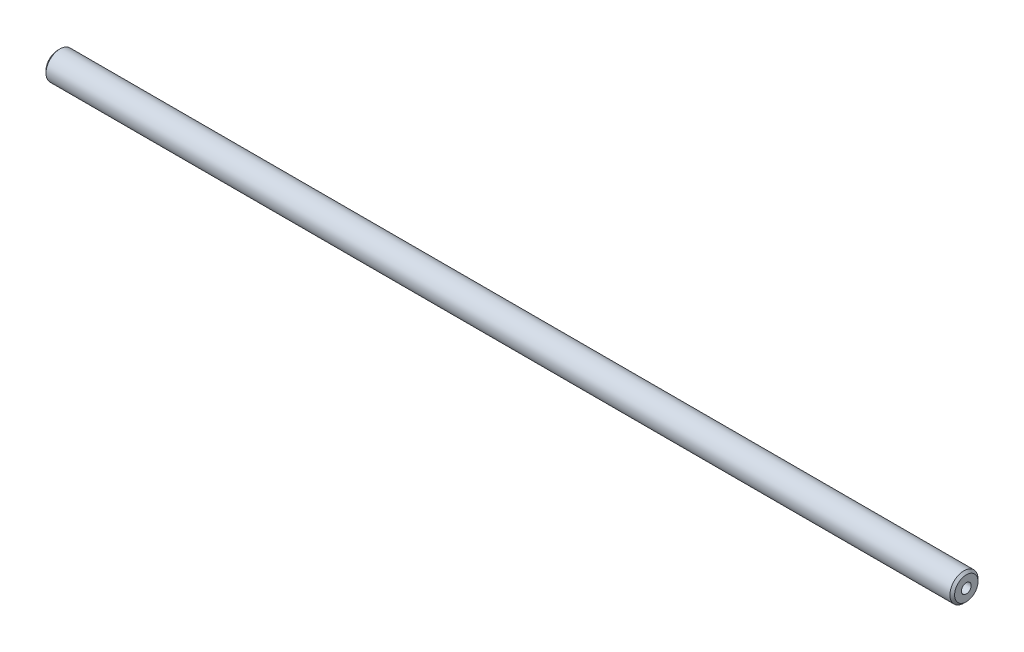
SolidWorks part; units mm, degrees
material "Chrome Stainless Steel"
ref_plane "Front Plane" through (0, 0, 0) normal (0, 0, 1) x (1, 0, 0)
ref_plane "Top Plane" through (0, 0, 0) normal (0, 1, 0) x (1, 0, 0)
ref_plane "Right Plane" through (0, 0, 0) normal (1, 0, 0) x (0, 0, -1)
sketch "Sketch1" plane through (0, 0, 0) normal (1, 0, 0) x (0, 0, -1)
  circle A0 centre (0, 0) radius 6
  dimension "D1" = 12
extrude "Boss-Extrude1" add sketch "Sketch1" along normal blind 388
chamfer "Chamfer1" distance 1 angle 45 2 edges at (388, 0, -6) (0, 0, -6)
hole_wizard "M5 Tapped Hole1" positions "Sketch3" profile "Sketch2" tap size "M5" standard "ISO"
sketch "Sketch3" plane through (388, 0, 0) normal (1, 0, 0) x (0, 0, -1)
  point P1 (0, 0)
sketch "Sketch2" plane through (388, 0, 0) normal (0, 1, 0) x (0, 0, -1)
  line L0 (0, 0) -> (0, 15.2618)
  line L1 (0, 15.2618) -> (2.1, 14)
  line L2 (2.1, 14) -> (2.1, 0)
  line L5 (2.1, 0) -> (0, 0)
  line L10 (0, 15.2618) -> (-2.1, 14) construction
  line L11 (0, -6.35) -> (0, 107.95) construction
  dimension "Tap Drill Dia." = 4.2
  dimension "Tap Drill Depth" = 14
  dimension "Drill Angle" = 118
cosmetic thread "Hole Thread1" parameters "D1"=10, "D2"=5
hole_wizard "M5 Tapped Hole2" positions "Sketch5" profile "Sketch4" tap size "M5" standard "ISO"
sketch "Sketch5" plane through (0, 0, 0) normal (-1, 0, 0) x (0, 0, 1)
  point P1 (0, 0)
sketch "Sketch4" plane through (0, 0, 0) normal (0, 1, 0) x (0, 0, 1)
  line L0 (0, 0) -> (0, 15.2618)
  line L1 (0, 15.2618) -> (2.1, 14)
  line L2 (2.1, 14) -> (2.1, 0)
  line L5 (2.1, 0) -> (0, 0)
  line L10 (0, 15.2618) -> (-2.1, 14) construction
  line L11 (0, -6.35) -> (0, 107.95) construction
  dimension "Tap Drill Dia." = 4.2
  dimension "Tap Drill Depth" = 14
  dimension "Drill Angle" = 118
cosmetic thread "Hole Thread2" parameters "D1"=10, "D2"=5
